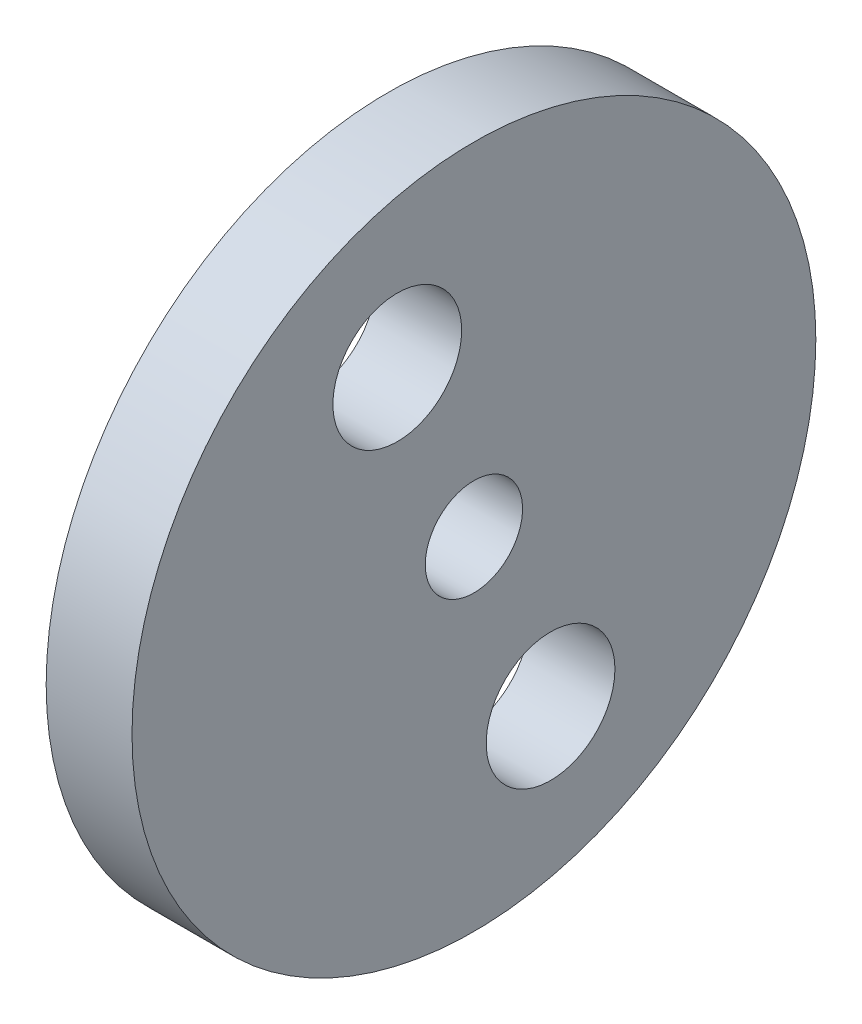
SolidWorks part; units mm, degrees
ref_plane "Front Plane" through (0, 0, 0) normal (0, 0, 1) x (1, 0, 0)
ref_plane "Top Plane" through (0, 0, 0) normal (0, 1, 0) x (1, 0, 0)
ref_plane "Right Plane" through (0, 0, 0) normal (1, 0, 0) x (0, 0, -1)
sketch "Axial profile (mm)" plane through (0, 0, 0) normal (0, 0, 1) x (1, 0, 0)
  line L0 (-110, 0) -> (75, 0) construction
  line L1 (73, 3.4) -> (79, 3.4)
  line L2 (79, 3.4) -> (79, 23.9)
  line L3 (79, 23.9) -> (73, 23.9)
  line L4 (73, 23.9) -> (73, 3.4)
revolve "Full revolution" add sketch "Axial profile (mm)" angle 360 about L0
sketch "Sketch2" plane through (0, 0, 0) normal (1, 0, 0) x (0, 0, -1)
  circle A0 centre (-5.3576, 12.9343) radius 4.5
  circle A1 centre (5.3576, -12.9343) radius 4.5
extrude "Axial holes" cut sketch "Sketch2" against normal through all and the other way through all
